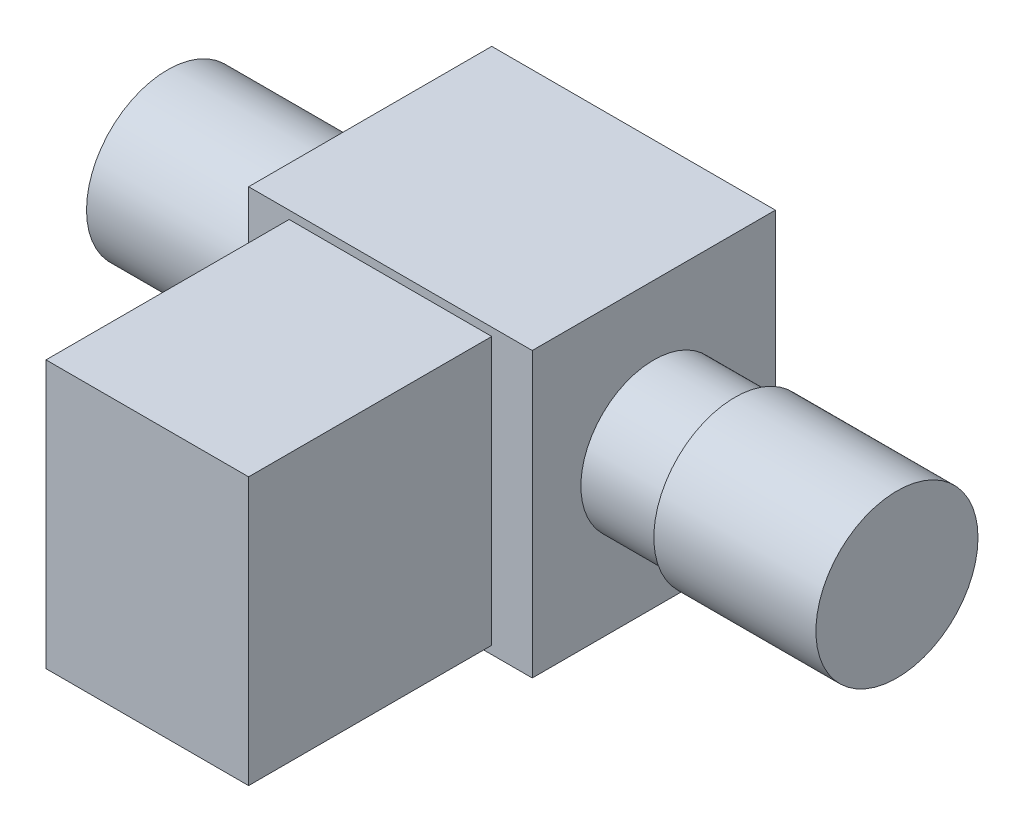
SolidWorks part; units mm, degrees
material "Aluminum Bronze"
ref_plane "Front Plane" through (0, 0, 0) normal (0, 0, 1) x (1, 0, 0)
ref_plane "Top Plane" through (0, 0, 0) normal (0, 1, 0) x (1, 0, 0)
ref_plane "Right Plane" through (0, 0, 0) normal (1, 0, 0) x (0, 0, -1)
sketch "Sketch1" plane through (0, 0, 0) normal (0, 0, 1) x (1, 0, 0)
  line L1 (-17.5, -17.5) -> (17.5, -17.5)
  line L2 (-17.5, -17.5) -> (-17.5, 17.5)
  line L3 (-17.5, 17.5) -> (17.5, 17.5)
  line L4 (17.5, -17.5) -> (17.5, 17.5)
  line L5 (-17.5, -17.5) -> (17.5, 17.5) construction
  line L6 (-17.5, 17.5) -> (17.5, -17.5) construction
  point P0 (0, 0)
  dimension "D1" = 35
  dimension "D2" = 35
extrude "Boss-Extrude1" add sketch "Sketch1" along normal blind 30
sketch "Sketch2" plane through (0, 0, 30) normal (0, 0, 1) x (1, 0, 0)
  line L0 (-17.5, 17.5) -> (17.5, -17.5) construction
  line L1 (17.5, 17.5) -> (-17.5, 17.5) construction
  line L2 (-12.5, -17.5) -> (12.5, -17.5)
  line L3 (-12.5, -17.5) -> (-12.5, 17.5)
  line L4 (-12.5, 17.5) -> (12.5, 17.5)
  line L5 (12.5, -17.5) -> (12.5, 17.5)
  line L6 (-12.5, -17.5) -> (12.5, 17.5) construction
  line L7 (-12.5, 17.5) -> (12.5, -17.5) construction
  point P4 (0, 0)
  dimension "D1" = 25
extrude "Boss-Extrude2" add sketch "Sketch2" along normal blind 30
sketch "Sketch3" plane through (-17.5, 0, 0) normal (-1, 0, 0) x (0, 0, 1)
  line L0 (30, 17.5) -> (0, -17.5) construction
  circle A0 centre (15, 0) radius 10
  dimension "D1" = 20
extrude "Boss-Extrude3" add sketch "Sketch3" along normal blind 25
sketch "Sketch4" plane through (17.5, 0, 0) normal (1, 0, 0) x (0, 0, -1)
  circle A1 centre (-15, 0) radius 10
  circle A2 centre (-15, 0) radius 10
  dimension "D1" = 0
extrude "Boss-Extrude4" add sketch "Sketch4" along normal blind 30
sketch "Sketch5" plane through (17.5, 0, 0) normal (1, 0, 0) x (0, 0, -1)
  line L4 (0, -17.5) -> (0, 17.5)
  line L5 (0, 17.5) -> (-30, 17.5)
  line L6 (-30, 17.5) -> (-30, -17.5)
  line L7 (-30, -17.5) -> (0, -17.5)
  line L8 (0, -17.5) -> (0, 17.5)
  line L9 (0, 17.5) -> (-30, 17.5)
  line L10 (-30, 17.5) -> (-30, -17.5)
  line L11 (-30, -17.5) -> (0, -17.5)
  circle A0 centre (-15, 0) radius 9
  circle A1 centre (-15, 0) radius 10
  circle A2 centre (-15, 0) radius 10
  circle M6 centre (-15, 0) radius 10
  dimension "D3" = 18
  dimension "D1" = 0
  dimension "D2" = 0
extrude "Cut-Extrude1" cut sketch "Sketch5" along normal blind 10 contours A0 M6
sketch "Sketch6" plane through (0, 0, 60) normal (0, 0, 1) x (1, 0, 0)
  line L0 (12.5, -17.5) -> (12.5, 17.5) construction
  line L1 (-12.5, 16.5) -> (12.5, 16.5)
  line L2 (-12.5, 16.5) -> (-12.5, -16.5)
  line L3 (-12.5, -16.5) -> (12.5, -16.5)
  line L4 (12.5, 16.5) -> (12.5, -16.5)
  line L5 (-12.5, 16.5) -> (12.5, -16.5) construction
  line L6 (-12.5, -16.5) -> (12.5, 16.5) construction
  line L7 (12.5, 17.5) -> (-12.5, 17.5) construction
  line L12 (12.5, -17.5) -> (12.5, 17.5)
  line L13 (12.5, 17.5) -> (-12.5, 17.5)
  line L14 (-12.5, 17.5) -> (-12.5, -17.5)
  line L15 (-12.5, -17.5) -> (12.5, -17.5)
  line L16 (12.5, -17.5) -> (12.5, 17.5)
  line L17 (12.5, 17.5) -> (-12.5, 17.5)
  line L18 (-12.5, 17.5) -> (-12.5, -17.5)
  line L19 (-12.5, -17.5) -> (12.5, -17.5)
  point P0 (0, 0)
  line M9 (12.5, -17.5) -> (12.5, 17.5)
  line M10 (12.5, 17.5) -> (-12.5, 17.5)
  line M11 (-12.5, 17.5) -> (-12.5, -17.5)
  line M12 (-12.5, -17.5) -> (12.5, -17.5)
  dimension "D1" = 1
  dimension "D2" = 0
extrude "Cut-Extrude2" cut sketch "Sketch6" against normal up to vertex (30 mm away) contours L1 M11 M9 M10 | L3 M11 M12 M9
